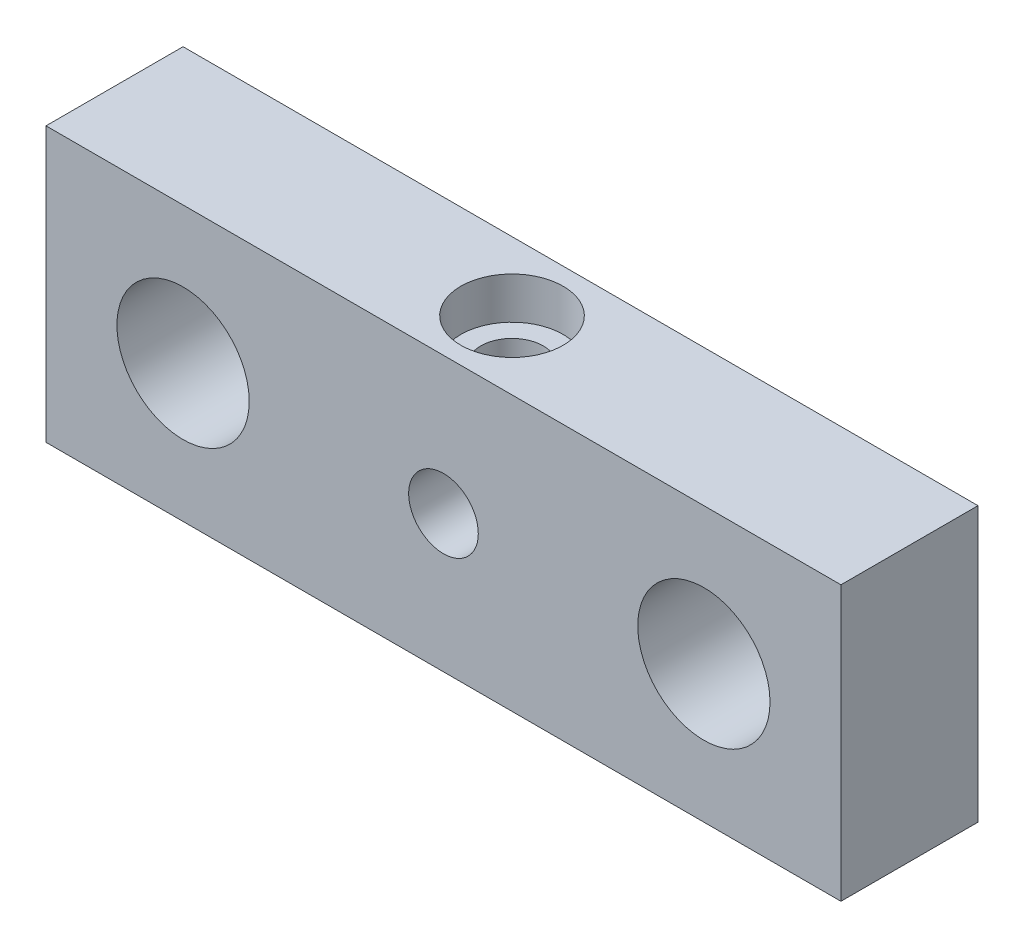
SolidWorks part; units mm, degrees
ref_plane "Front Plane" through (0, 0, 0) normal (0, 0, 1) x (1, 0, 0)
ref_plane "Top Plane" through (0, 0, 0) normal (0, 1, 0) x (1, 0, 0)
ref_plane "Right Plane" through (0, 0, 0) normal (1, 0, 0) x (0, 0, -1)
sketch "Sketch1" plane through (0, 0, 0) normal (0, 0, 1) x (1, 0, 0)
  line L1 (-14.5, 5) -> (14.5, 5)
  line L2 (-14.5, 5) -> (-14.5, -5)
  line L3 (-14.5, -5) -> (14.5, -5)
  line L4 (14.5, 5) -> (14.5, -5)
  dimension "D1" = 29
  dimension "D2" = 10
  dimension "D3" = 5
  dimension "D4" = 14.5
extrude "Boss-Extrude1" add sketch "Sketch1" along normal blind 5
sketch "Sketch2" plane through (0, 0, 5) normal (0, 0, 1) x (1, 0, 0)
  line L0 (-14.5, 5) -> (-14.5, -5) construction
  line L1 (14.5, -5) -> (14.5, 5) construction
  line L2 (14.5, 5) -> (-14.5, 5) construction
  circle A0 centre (-9.5, 0) radius 2.413
  circle A1 centre (9.5, 0) radius 2.413
  dimension "D1" = 4.826
  dimension "D2" = 5
  dimension "D3" = 5
  dimension "D4" = 5
  dimension "D5" = 5
extrude "Cut-Extrude1" cut sketch "Sketch2" against normal through all
sketch "Sketch3" plane through (0, 0, 5) normal (0, 0, 1) x (1, 0, 0)
  circle A0 centre (0, 0) radius 1.27
  dimension "D1" = 2.54
extrude "Cut-Extrude2" cut sketch "Sketch3" against normal through all
sketch "Sketch4" plane through (0, 5, 0) normal (0, 1, 0) x (1, 0, 0)
  line L0 (14.5, 0) -> (-14.5, 0) construction
  line L1 (-14.5, -5) -> (-14.5, 0) construction
  circle A0 centre (0, -2.5) radius 1.8669
  dimension "D2" = 3.7338
  dimension "D1" = 2.5
  dimension "D3" = 14.5
extrude "Cut-Extrude3" cut sketch "Sketch4" against normal blind 1.524
sketch "Sketch5" plane through (0, 3.476, 0) normal (0, 1, 0) x (1, 0, 0)
  line L0 (14.5, -5) -> (-14.5, -5) construction
  line L1 (14.5, -5) -> (14.5, 0) construction
  circle A0 centre (0, -2.5) radius 1.143
  dimension "D2" = 2.286
  dimension "D1" = 2.5
  dimension "D3" = 14.5
extrude "Cut-Extrude4" cut sketch "Sketch5" against normal up to next
